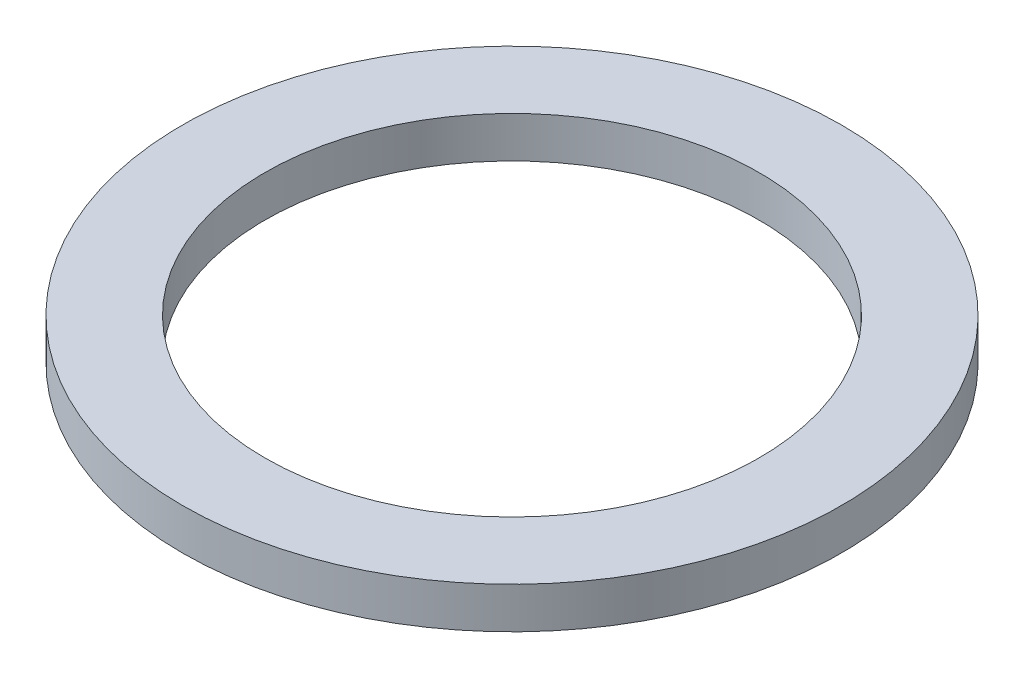
SolidWorks part; units mm, degrees
ref_plane "Front Plane" through (0, 0, 0) normal (0, 0, 1) x (1, 0, 0)
ref_plane "Top Plane" through (0, 0, 0) normal (0, 1, 0) x (1, 0, 0)
ref_plane "Right Plane" through (0, 0, 0) normal (1, 0, 0) x (0, 0, -1)
sketch "Sketch1" plane through (0, 0, 0) normal (0, 1, 0) x (1, 0, 0)
  circle A0 centre (0, 0) radius 50.8
  circle A1 centre (0, 0) radius 38.1
  dimension "D1" = 101.6
  dimension "D2" = 76.2
extrude "Boss-Extrude1" add sketch "Sketch1" along normal mid plane 6.35
equation "\"airframeInnerDiameter\"= 6in"
equation "\"outerDiameter\"= 6.112in"
equation "\"airframeBulkheadThickness\"= 0.125in"
equation "\"payloadAirframeLength\"= 10in"
equation "\"payloadInnerDiameter\"= 6in - 0.056in"
equation "\"payloadOuterDiameter\"= \"airframeInnerDiameter\""
equation "\"payloadLength\"= 11in"
equation "\"payloadBand\"= 2in"
equation "\"payloadOffsetFromAft\"= 6in"
equation "\"upperAirframeLength\"= 25in"
equation "\"recoveryBayInnerDiameter\"= 5.888in"
equation "\"recoveryLength\"= 8in"
equation "\"recoveryBand\"= 2in"
equation "\"recoveryCouplerOuter\"=\"airframeInnerDiameter\""
equation "\"recoveryOffsetFromAft\"= 3in"
equation "\"midAirframeLength\"= 20in"
equation "\"atsLength\"= 11in"
equation "\"atsInner\"= 5.888in"
equation "\"atsBand\"= 2in"
equation "\"atsCouplerOuter\"=\"airframeInnerDiameter\""
equation "\"atsOffsetFromAft\"= 3in"
equation "\"lowerAirframeLength\"= 40in"
equation "\"motorTubeOuterDiameter\"= 4.25in"
equation "\"motorTubeInnerDiameter\"= 4in"
equation "\"motorTubeLength\"= 32in"
equation "\"centeringRingOuterDiameter\"= \"airframeInnerDiameter\""
equation "\"centeringRingInnerDiameter\"= \"motorTubeOuterDiameter\""
equation "\"centeringRingThickness\"= 0.375in"
equation "\"topCenteringRingOffsetFromAft\"= 16.7in"
equation "\"bottomCenteringRingOffsetFromAft\"= 0.3in"
equation "\"finSlotLength\"= 8in"
equation "\"finSlotOffsetFromAft\"= 3in"
equation "\"finSlotWidth\"= 0.187in"
equation "\"motorCasingOuterDiameter\"= 3in"
equation "\"motorCasingCenteringRingThickness\"= 0.25in"
equation "\"D1@Sketch1\"=\"motorTubeInnerDiameter\""
equation "\"D2@Sketch1\"=\"motorCasingOuterDiameter\""
equation "\"D1@Boss-Extrude1\"=\"motorCasingCenteringRingThickness\""
